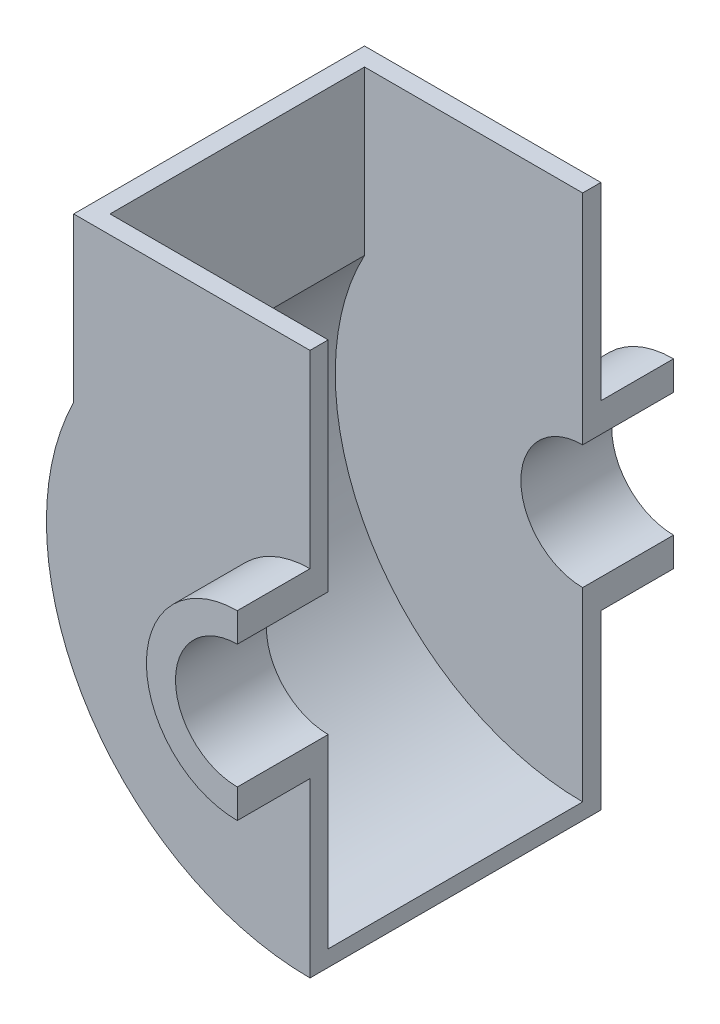
SolidWorks part; units mm, degrees
ref_plane "Front Plane" through (0, 0, 0) normal (0, 0, 1) x (1, 0, 0)
ref_plane "Top Plane" through (0, 0, 0) normal (0, 1, 0) x (1, 0, 0)
ref_plane "Right Plane" through (0, 0, 0) normal (1, 0, 0) x (0, 0, -1)
sketch "Sketch1" plane through (0, 0, 0) normal (0, 0, 1) x (1, 0, 0)
  line L0 (0, 25) -> (0, 17)
  line L1 (0, -17) -> (0, -25)
  arc A0 (0, 25) -> (0, -25) centre (0, 0) ccw
  arc A1 (0, 17) -> (0, -17) centre (0, 0) ccw
  dimension "D1" = 50
  dimension "D2" = 34
extrude "Boss-Extrude1" add sketch "Sketch1" along normal blind 20 and the other way blind 5
sketch "Sketch2" plane through (0, 0, 0) normal (0, 0, 1) x (1, 0, 0)
  line L0 (0, -25) -> (0, -72.5)
  line L1 (0, 25) -> (0, 77)
  line L2 (0, 77) -> (-65, 77)
  line L3 (-65, 77) -> (-65, 32.1131)
  line L6 (0, 17) -> (0, 25)
  line L7 (0, -25) -> (0, -17)
  line L8 (0, 17) -> (0, 25)
  line L9 (0, -25) -> (0, -17)
  arc A0 (-65, 32.1131) -> (0, -72.5) centre (0, 0) ccw
  arc A3 (0, 17) -> (0, -17) centre (0, 0) ccw
  arc A4 (0, 25) -> (0, -25) centre (0, 0) ccw
  arc A5 (0, 17) -> (0, -17) centre (0, 0) ccw
  dimension "D1" = 145
  dimension "D2" = 52
  dimension "D3" = 65
  dimension "D4" = 0
extrude "Boss-Extrude2" add sketch "Sketch2" against normal blind 5
ref_plane "Plane2" through (0, 0, -40) normal (0, 0, 1) x (1, 0, 0)
mirror "Mirror8" about plane through (0, 0, -40) normal (0, 0, 1) of bodies 102
sketch "Sketch3" plane through (0, 0, -75) normal (0, 0, 1) x (1, 0, 0)
  line L0 (-65, 32.1131) -> (-65, 77)
  line L1 (-65, 77) -> (-60, 77)
  line L2 (0, 77) -> (-65, 77) construction
  line L3 (-60, 77) -> (-60, 32.1131)
  line L4 (0, -68.0533) -> (0, -72.5)
  arc A1 (-60, 32.1131) -> (0, -68.0533) centre (0, 0) ccw
  arc A7 (-65, 32.1131) -> (0, -72.5) centre (0, 0) ccw
extrude "Boss-Extrude3" add sketch "Sketch3" along normal up to surface (70 mm away) up to face at (-29.3468, 15.924, -5)
